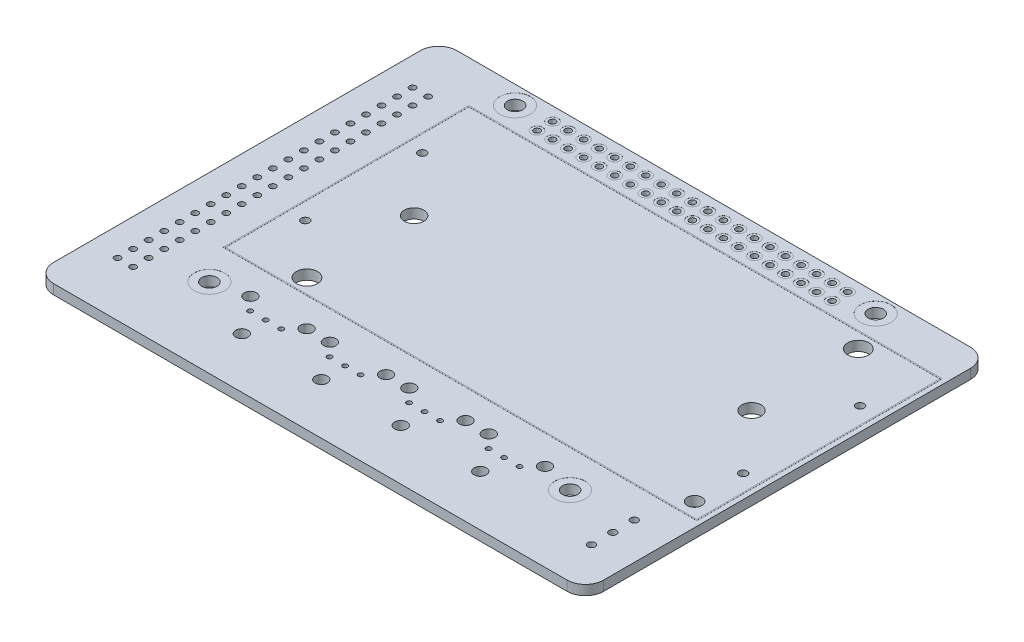
SolidWorks part; units mm, degrees
other "PCB" parameters "D3"=0.9122, "D6"=0.8536, "D10"=1.02, "D1"=23.2098, "D2"=50, "D4"=1.2925, "D5"=2.3249, "D8"=21.1581, "D9"=48.26, "D7"=20
ref_plane "Front Plane" through (0, 0, 0) normal (0, 0, 1) x (1, 0, 0)
ref_plane "Top Plane" through (0, 0, 0) normal (0, 1, 0) x (1, 0, 0)
ref_plane "Right Plane" through (0, 0, 0) normal (1, 0, 0) x (0, 0, -1)
sketch "Sketch1" plane through (0, 0, 0) normal (0, 1, 0) x (1, 0, 0)
  line L0 (0, 0) -> (0, 28) construction
  line L1 (-29.5, -28) -> (29.5, -28)
  line L2 (-32.5, -25) -> (-32.5, 25)
  line L3 (-29.5, 28) -> (29.5, 28)
  line L4 (32.5, -25) -> (32.5, 25)
  line L5 (-32.5, -28) -> (32.5, 28) construction
  line L6 (-32.5, 28) -> (32.5, -28) construction
  line L7 (0, 0) -> (32.5, 0) construction
  arc A0 (-29.5, -28) -> (-32.5, -25) centre (-29.5, -25) cw
  arc A1 (29.5, -28) -> (32.5, -25) centre (29.5, -25) ccw
  arc A2 (29.5, 28) -> (32.5, 25) centre (29.5, 25) cw
  arc A3 (-32.5, 25) -> (-29.5, 28) centre (-29.5, 25) cw
  circle A4 centre (-29.5, 25) radius 1.25
  circle A5 centre (29.5, 25) radius 1.25
  circle A6 centre (29.5, -25) radius 1.25
  circle A7 centre (-29.5, -25) radius 1.25
  point P0 (0, 0)
  dimension "D3" = 3
  dimension "D4" = 2.5
  dimension "D1" = 56
  dimension "D2" = 65
extrude "PCB-Outline" add sketch "Sketch1" along normal blind 1.6
sketch "Sketch2" plane through (0, 1.6, 0) normal (0, 1, 0) x (1, 0, 0)
  line L0 (-29.5, -28) -> (29.5, -28) construction
  line L1 (-32.5, 25) -> (-32.5, -25) construction
  line L2 (-24.13, 25.77) -> (-24.13, 23.23) construction
  line L3 (0, 24.5) -> (-24.13, 24.5) construction
  circle A0 centre (-24.13, 25.77) radius 0.51
  circle A1 centre (-24.13, 23.23) radius 0.51
  circle A2 centre (-21.59, 25.77) radius 0.51
  circle A3 centre (-21.59, 23.23) radius 0.51
  circle A4 centre (-19.05, 25.77) radius 0.51
  circle A5 centre (-19.05, 23.23) radius 0.51
  circle A6 centre (-16.51, 25.77) radius 0.51
  circle A7 centre (-16.51, 23.23) radius 0.51
  circle A8 centre (-13.97, 25.77) radius 0.51
  circle A9 centre (-13.97, 23.23) radius 0.51
  circle A10 centre (-11.43, 25.77) radius 0.51
  circle A11 centre (-11.43, 23.23) radius 0.51
  circle A12 centre (-8.89, 25.77) radius 0.51
  circle A13 centre (-8.89, 23.23) radius 0.51
  circle A14 centre (-6.35, 25.77) radius 0.51
  circle A15 centre (-6.35, 23.23) radius 0.51
  circle A16 centre (-3.81, 25.77) radius 0.51
  circle A17 centre (-3.81, 23.23) radius 0.51
  circle A18 centre (-1.27, 25.77) radius 0.51
  circle A19 centre (-1.27, 23.23) radius 0.51
  circle A20 centre (1.27, 25.77) radius 0.51
  circle A21 centre (1.27, 23.23) radius 0.51
  circle A22 centre (3.81, 25.77) radius 0.51
  circle A23 centre (3.81, 23.23) radius 0.51
  circle A24 centre (6.35, 25.77) radius 0.51
  circle A25 centre (6.35, 23.23) radius 0.51
  circle A26 centre (8.89, 25.77) radius 0.51
  circle A27 centre (8.89, 23.23) radius 0.51
  circle A28 centre (11.43, 25.77) radius 0.51
  circle A29 centre (11.43, 23.23) radius 0.51
  circle A30 centre (13.97, 25.77) radius 0.51
  circle A31 centre (13.97, 23.23) radius 0.51
  circle A32 centre (16.51, 25.77) radius 0.51
  circle A33 centre (16.51, 23.23) radius 0.51
  circle A34 centre (19.05, 25.77) radius 0.51
  circle A35 centre (19.05, 23.23) radius 0.51
  circle A36 centre (21.59, 25.77) radius 0.51
  circle A37 centre (21.59, 23.23) radius 0.51
  circle A38 centre (24.13, 25.77) radius 0.51
  circle A39 centre (24.13, 23.23) radius 0.51
  point P0 (0, 24.5)
  point P12 (-24.13, 24.5)
  dimension "D3" = 1.02
  dimension "D6" = 1.02
  dimension "D1" = 52.5
  dimension "D2" = 32.5
  dimension "D4" = 1.27
  dimension "D5" = 2.54
  dimension "D8" = 24.13
  dimension "D9" = 48.26
  dimension "D10" = 2.54
extrude "40-Pin-Holes" cut sketch "Sketch2" against normal through all
sketch "Sketch8" plane through (0, 1.6, 0) normal (0, 1, 0) x (1, 0, 0)
  line L0 (-24.13, 25.77) -> (-24.13, 23.23) construction
  circle A0 centre (-24.13, 25.77) radius 0.91
  circle A1 centre (-24.13, 25.77) radius 0.51 construction
  circle A4 centre (-21.59, 25.77) radius 0.91
  circle A5 centre (-19.05, 25.77) radius 0.91
  circle A6 centre (-16.51, 25.77) radius 0.91
  circle A7 centre (-13.97, 25.77) radius 0.91
  circle A8 centre (-11.43, 25.77) radius 0.91
  circle A9 centre (-8.89, 25.77) radius 0.91
  circle A10 centre (-6.35, 25.77) radius 0.91
  circle A11 centre (-3.81, 25.77) radius 0.91
  circle A12 centre (-1.27, 25.77) radius 0.91
  circle A13 centre (1.27, 25.77) radius 0.91
  circle A14 centre (3.81, 25.77) radius 0.91
  circle A15 centre (6.35, 25.77) radius 0.91
  circle A16 centre (8.89, 25.77) radius 0.91
  circle A17 centre (11.43, 25.77) radius 0.91
  circle A18 centre (13.97, 25.77) radius 0.91
  circle A19 centre (16.51, 25.77) radius 0.91
  circle A20 centre (19.05, 25.77) radius 0.91
  circle A21 centre (21.59, 25.77) radius 0.91
  circle A22 centre (24.13, 25.77) radius 0.91
  circle A23 centre (-21.59, 23.23) radius 0.91
  circle A24 centre (-19.05, 23.23) radius 0.91
  circle A25 centre (-16.51, 23.23) radius 0.91
  circle A26 centre (-13.97, 23.23) radius 0.91
  circle A27 centre (-11.43, 23.23) radius 0.91
  circle A28 centre (-8.89, 23.23) radius 0.91
  circle A29 centre (-6.35, 23.23) radius 0.91
  circle A30 centre (-3.81, 23.23) radius 0.91
  circle A31 centre (-1.27, 23.23) radius 0.91
  circle A32 centre (1.27, 23.23) radius 0.91
  circle A33 centre (3.81, 23.23) radius 0.91
  circle A34 centre (6.35, 23.23) radius 0.91
  circle A35 centre (8.89, 23.23) radius 0.91
  circle A36 centre (11.43, 23.23) radius 0.91
  circle A37 centre (13.97, 23.23) radius 0.91
  circle A38 centre (16.51, 23.23) radius 0.91
  circle A39 centre (19.05, 23.23) radius 0.91
  circle A40 centre (21.59, 23.23) radius 0.91
  circle A41 centre (24.13, 23.23) radius 0.91
  circle A42 centre (-24.13, 23.23) radius 0.91
  dimension "D1" = 0.4
  dimension "D2" = 20
  dimension "D4" = 2.54
  dimension "D5" = 2.54
  dimension "D3" = 2
extrude "Cut-Extrude3" cut sketch "Sketch8" against normal blind 0.01
ref_plane "Plane1" through (0, 0.8, 0) normal (0, -1, 0) x (-1, 0, 0)
mirror "Mirror1" about plane through (0, 0.8, 0) normal (0, -1, 0) of "Cut-Extrude3"
sketch "Sketch9" plane through (0, 1.6, 0) normal (0, 1, 0) x (1, 0, 0)
  line L0 (0, -3.905) -> (0, 3.905) construction
  line L1 (-3.905, 0) -> (3.905, 0) construction
  circle A0 centre (-29.5, 25) radius 2.5
  circle A3 centre (29.5, 25) radius 2.5
  circle A4 centre (29.5, -25) radius 2.5
  circle A5 centre (-29.5, -25) radius 2.5
  dimension "D1" = 5
extrude "Cut-Extrude4" cut sketch "Sketch9" against normal blind 0.01
mirror "Mirror2" about plane through (0, 0.8, 0) normal (0, -1, 0) of "Cut-Extrude4"
sketch "Sketch10" plane through (0, 1.6, 0) normal (0, 1, 0) x (1, 0, 0)
  line L0 (-29.5, 28) -> (-45, 28)
  line L1 (-45, 28) -> (-45, -28)
  line L2 (-45, -28) -> (-29.5, -28)
  line L3 (-32.5, 25) -> (-32.5, -25) construction
  line L4 (-32.5, 25) -> (-32.5, -25)
  line L5 (0, -0.88) -> (0, 0.88) construction
  line L6 (32.5, 25) -> (32.5, -25)
  line L7 (45, -28) -> (29.5, -28)
  line L8 (45, 28) -> (45, -28)
  line L9 (29.5, 28) -> (45, 28)
  arc A0 (-32.5, -25) -> (-29.5, -28) centre (-29.5, -25) ccw construction
  arc A1 (-29.5, 28) -> (-32.5, 25) centre (-29.5, 25) ccw construction
  arc A2 (-32.5, -25) -> (-29.5, -28) centre (-29.5, -25) ccw
  arc A3 (-29.5, 28) -> (-32.5, 25) centre (-29.5, 25) ccw
  arc A4 (29.5, 28) -> (32.5, 25) centre (29.5, 25) cw
  arc A5 (32.5, -25) -> (29.5, -28) centre (29.5, -25) cw
  point P20 (-45, 28)
  dimension "D1" = 90
extrude "Boss-Extrude1" add sketch "Sketch10" against normal blind 1.6
fillet "Fillet1" radius 3 4 edges at (-45, 0.8, 28) (-45, 0.8, -28) (45, 0.8, -28) (45, 0.8, 28)
sketch "Sketch11" plane through (0, 1.6, 0) normal (0, 1, 0) x (1, 0, 0)
  line L1 (-33.06, 21) -> (44, 21) construction
  line L2 (-33.06, 21) -> (-33.06, -18.78) construction
  line L3 (-33.06, -18.78) -> (44, -18.78) construction
  line L4 (44, 21) -> (44, -18.78) construction
  line L5 (42, 28) -> (-42, 28) construction
  line L6 (-30.35, 10.66) -> (41.29, 10.66) construction
  line L7 (-30.35, -8.47) -> (41.29, -8.47) construction
  line L8 (-30.35, 10.66) -> (-30.35, -8.47) construction
  line L9 (-22.13, -16.42) -> (41.29, -16.42) construction
  line L10 (-22.13, 1.11) -> (33.07, 1.11) construction
  line L11 (33.07, 1.11) -> (33.07, 18.58) construction
  line L12 (-22.13, 1.11) -> (-22.13, -16.42) construction
  line L13 (33.07, 1.11) -> (44, 1.11) construction
  line L14 (41.29, 10.66) -> (41.29, -8.47) construction
  line L15 (41.29, -16.42) -> (41.29, -8.47) construction
  line L16 (5.47, 21) -> (5.47, 10.66) construction
  line L17 (-22.13, 1.11) -> (-33.06, 1.11) construction
  line L18 (5.47, 10.66) -> (5.47, 1.11) construction
  line L19 (45, -25) -> (45, 25) construction
  circle A0 centre (-22.13, -16.42) radius 1.725
  circle A1 centre (33.07, 18.58) radius 1.725
  circle A2 centre (41.29, -16.42) radius 1.19
  circle A3 centre (41.29, -8.47) radius 0.66
  circle A4 centre (-30.35, -8.47) radius 0.66
  circle A5 centre (-30.35, 10.66) radius 0.66
  circle A6 centre (41.29, 10.66) radius 0.66
  circle A7 centre (-22.13, 1.11) radius 1.59
  circle A8 centre (33.07, 1.11) radius 1.59
  dimension "D3" = 3.18
  dimension "D4" = 3.45
  dimension "D5" = 3.18
  dimension "D6" = 3.45
  dimension "D7" = 2.38
  dimension "D8" = 1.32
  dimension "D9" = 1.32
  dimension "D10" = 1.32
  dimension "D11" = 1.32
  dimension "D1" = 77.06
  dimension "D2" = 39.78
  dimension "D12" = 35
  dimension "D13" = 55.2
  dimension "D14" = 71.64
  dimension "D15" = 19.13
  dimension "D16" = 7.95
  dimension "D17" = 9.55
  dimension "D18" = 7
  dimension "D19" = 1
extrude "Cut-Extrude5" cut sketch "Sketch11" against normal blind 1.6 contours A5 | A1 | A6 | A8 | A3 | A2 | A0 | A7 | A4
sketch "Sketch12" plane through (0, 1.6, 0) normal (0, 1, 0) x (1, 0, 0)
  line L0 (-33.26, 21.2) -> (-33.26, -18.98)
  line L1 (-33.06, 21) -> (44, 21)
  line L2 (-33.06, 21) -> (-33.06, -18.78)
  line L3 (-33.06, -18.78) -> (44, -18.78)
  line L4 (44, 21) -> (44, -18.78)
  line L5 (-33.26, -18.98) -> (44.2, -18.98)
  line L6 (44.2, 21.2) -> (44.2, -18.98)
  line L7 (-33.26, 21.2) -> (44.2, 21.2)
  dimension "D1" = 0.2
extrude "Boss-Extrude2" add sketch "Sketch12" along normal blind 0.01
sketch "Sketch13" plane through (0, 1.6, 0) normal (0, 1, 0) x (1, 0, 0)
  line L0 (-45, -25) -> (-45, -35)
  line L1 (-42, -38) -> (42, -38)
  line L2 (45, -35) -> (45, -25)
  line L3 (-42, -28) -> (42, -28) construction
  line L4 (-42, -28) -> (42, -28)
  arc A0 (42, -28) -> (45, -25) centre (42, -25) ccw construction
  arc A1 (-45, -25) -> (-42, -28) centre (-42, -25) ccw construction
  arc A2 (-45, -25) -> (-42, -28) centre (-42, -25) ccw
  arc A3 (42, -28) -> (45, -25) centre (42, -25) ccw
  arc A4 (42, -38) -> (45, -35) centre (42, -35) ccw
  arc A5 (-45, -35) -> (-42, -38) centre (-42, -35) ccw
  dimension "D2" = 3
  dimension "D1" = 10
extrude "Boss-Extrude3" add sketch "Sketch13" against normal blind 1.6
sketch "Sketch14" plane through (0, 1.6, 0) normal (0, 1, 0) x (1, 0, 0)
  line L0 (-24.1, -23.7) -> (-14.9, -23.7) construction
  line L1 (-19.5, -23.7) -> (-19.5, -29.7) construction
  line L2 (-22.04, -25.8) -> (-16.96, -25.8) construction
  line L3 (-6.5, -23.7) -> (-6.5, -29.7) construction
  line L4 (-9.04, -25.8) -> (-3.96, -25.8) construction
  line L5 (6.5, -23.7) -> (6.5, -29.7) construction
  line L6 (3.96, -25.8) -> (9.04, -25.8) construction
  line L7 (19.5, -23.7) -> (19.5, -29.7) construction
  line L8 (16.96, -25.8) -> (22.04, -25.8) construction
  line L9 (-1.9, -23.7) -> (1.9, -23.7) construction
  line L10 (0, -38) -> (0, -23.7) construction
  line L11 (-42, -38) -> (42, -38) construction
  circle A0 centre (-24.1, -23.7) radius 1
  circle A1 centre (-14.9, -23.7) radius 1
  circle A2 centre (-19.5, -29.7) radius 1
  circle A3 centre (-22.04, -25.8) radius 0.4
  circle A4 centre (-19.5, -25.8) radius 0.4
  circle A5 centre (-16.96, -25.8) radius 0.4
  circle A6 centre (-11.1, -23.7) radius 1
  circle A7 centre (-1.9, -23.7) radius 1
  circle A8 centre (-6.5, -29.7) radius 1
  circle A9 centre (-9.04, -25.8) radius 0.4
  circle A10 centre (-6.5, -25.8) radius 0.4
  circle A11 centre (-3.96, -25.8) radius 0.4
  circle A12 centre (1.9, -23.7) radius 1
  circle A13 centre (11.1, -23.7) radius 1
  circle A14 centre (6.5, -29.7) radius 1
  circle A15 centre (3.96, -25.8) radius 0.4
  circle A16 centre (6.5, -25.8) radius 0.4
  circle A17 centre (9.04, -25.8) radius 0.4
  circle A18 centre (14.9, -23.7) radius 1
  circle A19 centre (24.1, -23.7) radius 1
  circle A20 centre (19.5, -29.7) radius 1
  circle A21 centre (16.96, -25.8) radius 0.4
  circle A22 centre (19.5, -25.8) radius 0.4
  circle A23 centre (22.04, -25.8) radius 0.4
  dimension "D1" = 0.8
  dimension "D2" = 0.8
  dimension "D3" = 0.8
  dimension "D6" = 2
  dimension "D7" = 2
  dimension "D8" = 2
  dimension "D4" = 9.2
  dimension "D5" = 6
  dimension "D9" = 2.54
  dimension "D10" = 3.9
  dimension "D12" = 14.3
  dimension "D13" = 13
  dimension "D11" = 4
extrude "Cut-Extrude6" cut sketch "Sketch14" against normal blind 1.6
sketch "Sketch15" plane through (0, 0, 0) normal (0, -1, 0) x (1, 0, 0)
  line L0 (39, 31) -> (39, 24) construction
  line L1 (45, 35) -> (45, -25) construction
  line L2 (-42, 38) -> (42, 38) construction
  circle A0 centre (39, 31) radius 0.6
  circle A1 centre (39, 24) radius 0.6
  circle A2 centre (39, 27.5) radius 0.6
  dimension "D1" = 1.2
  dimension "D2" = 1.2
  dimension "D3" = 1.2
  dimension "D4" = 3.5
  dimension "D5" = 6
  dimension "D6" = 7
extrude "Cut-Extrude7" cut sketch "Sketch15" against normal blind 1.6
sketch "Sketch16" plane through (0, 1.6, 0) normal (0, 1, 0) x (1, 0, 0)
  line L0 (-40.4, 19.13) -> (-37.86, 19.13) construction
  line L1 (-45, 25) -> (-45, -35) construction
  line L2 (-39.13, 19.13) -> (-39.13, -29.13) construction
  line L3 (-39.13, -29.13) -> (-40.4, -29.13) construction
  line L4 (-45, -5) -> (-39.13, -5) construction
  circle A0 centre (-37.86, 19.13) radius 0.51
  circle A1 centre (-40.4, 19.13) radius 0.51
  circle A2 centre (-40.4, 16.59) radius 0.51
  circle A3 centre (-37.86, 16.59) radius 0.51
  circle A4 centre (-40.4, 14.05) radius 0.51
  circle A5 centre (-37.86, 14.05) radius 0.51
  circle A6 centre (-40.4, 11.51) radius 0.51
  circle A7 centre (-37.86, 11.51) radius 0.51
  circle A8 centre (-40.4, 8.97) radius 0.51
  circle A9 centre (-37.86, 8.97) radius 0.51
  circle A10 centre (-40.4, 6.43) radius 0.51
  circle A11 centre (-37.86, 6.43) radius 0.51
  circle A12 centre (-40.4, 3.89) radius 0.51
  circle A13 centre (-37.86, 3.89) radius 0.51
  circle A14 centre (-40.4, 1.35) radius 0.51
  circle A15 centre (-37.86, 1.35) radius 0.51
  circle A16 centre (-40.4, -1.19) radius 0.51
  circle A17 centre (-37.86, -1.19) radius 0.51
  circle A18 centre (-40.4, -3.73) radius 0.51
  circle A19 centre (-37.86, -3.73) radius 0.51
  circle A20 centre (-40.4, -6.27) radius 0.51
  circle A21 centre (-37.86, -6.27) radius 0.51
  circle A22 centre (-40.4, -8.81) radius 0.51
  circle A23 centre (-37.86, -8.81) radius 0.51
  circle A24 centre (-40.4, -11.35) radius 0.51
  circle A25 centre (-37.86, -11.35) radius 0.51
  circle A26 centre (-40.4, -13.89) radius 0.51
  circle A27 centre (-37.86, -13.89) radius 0.51
  circle A28 centre (-40.4, -16.43) radius 0.51
  circle A29 centre (-37.86, -16.43) radius 0.51
  circle A30 centre (-40.4, -18.97) radius 0.51
  circle A31 centre (-37.86, -18.97) radius 0.51
  circle A32 centre (-40.4, -21.51) radius 0.51
  circle A33 centre (-37.86, -21.51) radius 0.51
  circle A34 centre (-40.4, -24.05) radius 0.51
  circle A35 centre (-37.86, -24.05) radius 0.51
  circle A36 centre (-40.4, -26.59) radius 0.51
  circle A37 centre (-37.86, -26.59) radius 0.51
  circle A38 centre (-40.4, -29.13) radius 0.51
  circle A39 centre (-37.86, -29.13) radius 0.51
  point P5 (-39.13, 19.13)
  dimension "D1" = 1.02
  dimension "D2" = 1.02
  dimension "D3" = 2.54
  dimension "D5" = 5.87
  dimension "D6" = 2.54
  dimension "D4" = 20
extrude "Cut-Extrude8" cut sketch "Sketch16" against normal blind 1.6 contours A39
equation "\"D6@Sketch2\"=\"D3@Sketch2\""
equation "\"D8@Sketch2\"=\"D9@Sketch2\"/2"
